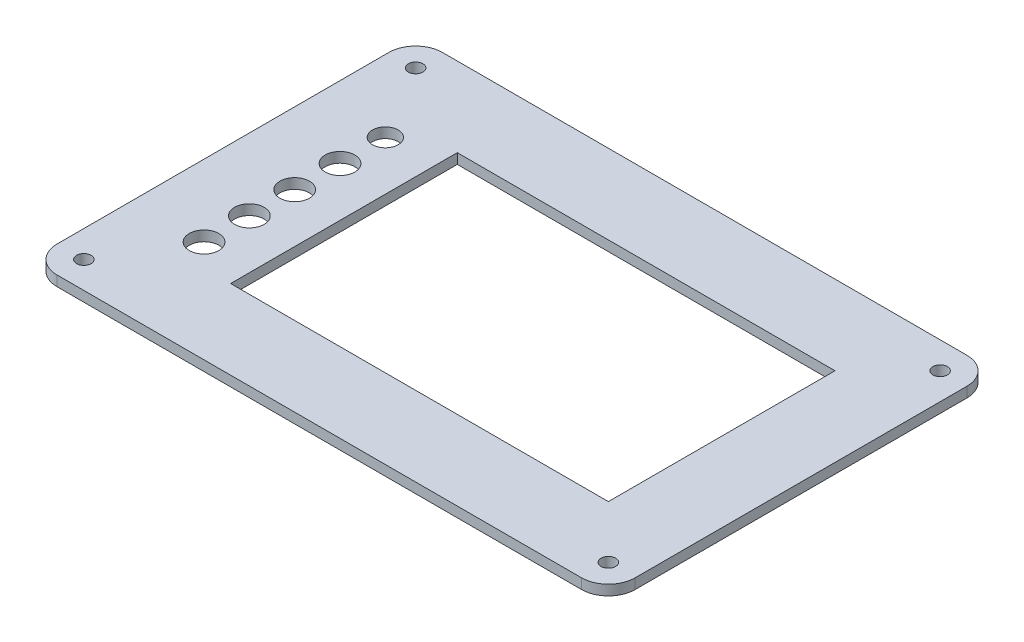
SolidWorks part; units mm, degrees
material "Plain Carbon Steel"
ref_plane "Front" through (0, 0, 0) normal (0, 0, 1) x (1, 0, 0)
ref_plane "Top" through (0, 0, 0) normal (0, 1, 0) x (1, 0, 0)
ref_plane "Right" through (0, 0, 0) normal (1, 0, 0) x (0, 0, -1)
sketch "Sketch1" plane through (0, 0, 0) normal (0, 1, 0) x (1, 0, 0)
  line L0 (-45, 0) -> (45, 0) construction
  line L1 (-45, 30) -> (45, 30) construction
  line L2 (-45, 30) -> (-45, -30) construction
  line L3 (-45, -30) -> (45, -30) construction
  line L4 (45, 30) -> (45, -30) construction
  line L5 (0, -30) -> (0, 30) construction
  line L6 (41.825, 26.825) -> (41.825, -26.825) construction
  line L7 (-41.825, -26.825) -> (41.825, -26.825) construction
  line L8 (-41.825, 26.825) -> (-41.825, -26.825) construction
  line L9 (-41.825, 26.825) -> (41.825, 26.825) construction
  line L10 (40.825, 25.825) -> (40.825, -25.825) construction
  line L11 (-40.825, -25.825) -> (40.825, -25.825) construction
  line L12 (-40.825, 25.825) -> (-40.825, -25.825) construction
  line L13 (-40.825, 25.825) -> (40.825, 25.825) construction
  line L14 (40.825, 21.65) -> (45, 21.65) construction
  line L15 (40.825, -21.65) -> (45, -21.65) construction
  line L16 (36.65, -25.825) -> (36.65, -30) construction
  line L17 (-36.65, -25.825) -> (-36.65, -30) construction
  line L18 (-40.825, -21.65) -> (-45, -21.65) construction
  line L19 (-36.65, 25.825) -> (-36.65, 30) construction
  line L20 (-40.825, 21.65) -> (-45, 21.65) construction
  line L21 (36.65, 25.825) -> (36.65, 30) construction
  line L22 (40.825, -25.825) -> (41.825, -25.825) construction
  circle A0 centre (-40.825, -25.825) radius 1 construction
  circle A1 centre (40.825, -25.825) radius 1 construction
  circle A2 centre (40.825, 25.825) radius 1 construction
  circle A3 centre (-40.825, 25.825) radius 1 construction
  circle A4 centre (40.825, -25.825) radius 4.175 construction
  circle A5 centre (40.825, 25.825) radius 4.175 construction
  circle A6 centre (-40.825, 25.825) radius 4.175 construction
  circle A7 centre (-40.825, -25.825) radius 4.175 construction
  dimension "D1" = 90
  dimension "D2" = 60
  dimension "D4" = 1
  dimension "D3" = 3.175
sketch "Sketch2" plane through (0, 0, 0) normal (0, 1, 0) x (1, 0, 0)
  line L0 (-45, 30) -> (-45, -30) construction
  line L1 (-45, -30) -> (45, -30) construction
  line L2 (45, 30) -> (45, -30) construction
  line L3 (-45, 30) -> (45, 30) construction
  line L16 (-45, 25.825) -> (-45, -25.825)
  line L17 (-40.825, -30) -> (40.825, -30)
  line L18 (45, 25.825) -> (45, -25.825)
  line L19 (-40.825, 30) -> (40.825, 30)
  circle A0 centre (40.825, 25.825) radius 4.175 construction
  circle A2 centre (-40.825, 25.825) radius 4.175 construction
  circle A4 centre (40.825, 25.825) radius 1.1303
  circle A5 centre (40.825, -25.825) radius 1.1303
  arc A6 (45, 25.825) -> (40.825, 30) centre (40.825, 25.825) ccw
  circle A7 centre (-40.825, 25.825) radius 1.1303
  arc A8 (-40.825, 30) -> (-45, 25.825) centre (-40.825, 25.825) ccw
  circle A9 centre (-40.825, -25.825) radius 1.1303
  arc A17 (-45, -25.825) -> (-40.825, -30) centre (-40.825, -25.825) ccw
  arc A18 (40.825, -30) -> (45, -25.825) centre (40.825, -25.825) ccw
  dimension "D1" = 2.2606
  dimension "D2" = 2.2606
  dimension "D3" = 2.2606
  dimension "D4" = 2.2606
extrude "Boss-Extrude3" add sketch "Sketch2" along normal blind 1.5875
sketch "Sketch3" plane through (0, 1.5875, 0) normal (0, 1, 0) x (1, 0, 0)
  line L0 (45, 0) -> (-45, 0) construction
  line L1 (-26.16, 17.64) -> (32.64, 17.64)
  line L2 (-26.16, 17.64) -> (-26.16, -17.64)
  line L3 (-26.16, -17.64) -> (32.64, -17.64)
  line L4 (32.64, 17.64) -> (32.64, -17.64)
  line L5 (-26.16, 17.64) -> (32.64, -17.64) construction
  line L6 (-26.16, -17.64) -> (32.64, 17.64) construction
  line L7 (45, -25.825) -> (45, 25.825) construction
  line L8 (-45, 25.825) -> (-45, -25.825) construction
  point P0 (3.24, 0)
  dimension "D1" = 58.8
  dimension "D2" = 35.28
  dimension "D3" = 12.36
sketch "Sketch4" plane through (0, 1.5875, 0) normal (0, 1, 0) x (1, 0, 0)
  circle A0 centre (-33.825, 7.053) radius 1.8 construction
  circle A1 centre (-33.825, -0.003) radius 1.8 construction
  circle A2 centre (-33.825, -7.059) radius 1.8 construction
  circle A3 centre (-33.825, -14.115) radius 1.8 construction
  circle A4 centre (-33.825, 14.109) radius 1.4986 construction
  circle A5 centre (-33.825, 7.053) radius 1.8 construction
  circle A6 centre (-33.825, -0.003) radius 1.8 construction
  circle A7 centre (-33.825, -7.059) radius 1.8 construction
  circle A8 centre (-33.825, -14.115) radius 1.8 construction
  circle A9 centre (-33.825, 14.109) radius 1.4986 construction
  circle A10 centre (-33.825, 14.109) radius 1.9986
  circle A11 centre (-33.825, 7.053) radius 2.3
  circle A12 centre (-33.825, -0.003) radius 2.3
  circle A13 centre (-33.825, -7.059) radius 2.3
  circle A14 centre (-33.825, -14.115) radius 2.3
  dimension "D1" = 0.5
extrude "Cut-Extrude1" cut sketch "Sketch4" against normal through all
extrude "Cut-Extrude2" cut sketch "Sketch3" against normal through all
sketch "Sketch5" plane through (0, 1.5875, 0) normal (0, 1, 0) x (1, 0, 0)
  line L0 (3.24, 17.64) -> (3.24, -17.64) construction
  line L1 (32.64, 17.64) -> (-26.16, 17.64) construction
  line L2 (-26.16, -17.64) -> (32.64, -17.64) construction
  line L3 (32.64, 0) -> (-26.16, 0) construction
  line L4 (32.64, -17.64) -> (32.64, 17.64) construction
  line L5 (-26.16, 17.64) -> (-26.16, -17.64) construction
hole_wizard "Tap Drill for #4-40 Tap1" positions "3DSketch1" profile "Sketch6" hole size "#4-40" standard "ANSI Inch" end condition through all
sketch3d "3DSketch1"
  line L0 (-40.825, 1.5875, 25.825) -> (-40.825, 0, 25.825) construction
  line L1 (-40.825, 1.5875, -25.825) -> (-40.825, 0, -25.825) construction
  line L2 (40.825, 1.5875, -25.825) -> (40.825, 0, -25.825) construction
  line L3 (40.825, 1.5875, 25.825) -> (40.825, 0, 25.825) construction
  point P0 (-40.825, 1.5875, 25.825)
  point P5 (-40.825, 1.5875, -25.825)
  point P10 (40.825, 1.5875, -25.825)
  point P15 (40.825, 1.5875, 25.825)
sketch "Sketch6" plane through (-40.825, 1.5875, 25.825) normal (1, 0, 0) x (0, 0, 1)
  line L0 (0, 0) -> (0, 1.5875)
  line L1 (0, 1.5875) -> (1.1303, 1.5875)
  line L2 (1.1303, 1.5875) -> (1.1303, 0)
  line L5 (1.1303, 0) -> (0, 0)
  line L11 (0, -6.35) -> (0, 107.95) construction
  dimension "Thru Hole Dia." = 2.2606
  dimension "Thru Hole Depth" = 1.5875
